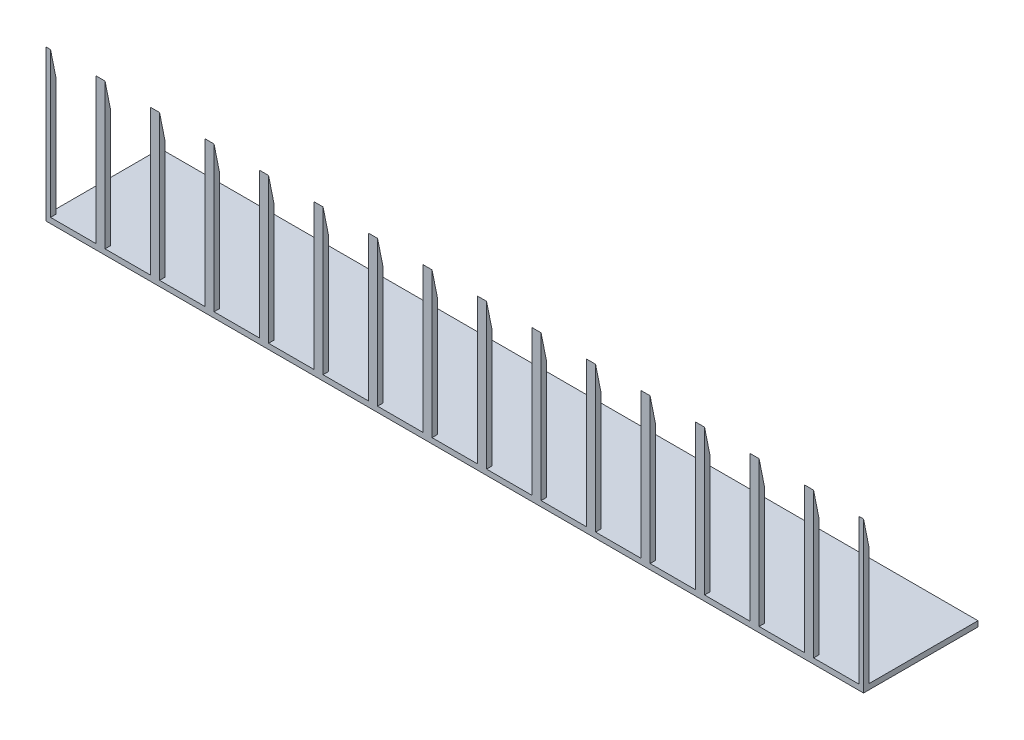
SolidWorks part; units mm, degrees
ref_plane "前视基准面" through (0, 0, 0) normal (0, 0, 1) x (1, 0, 0)
ref_plane "上视基准面" through (0, 0, 0) normal (0, 1, 0) x (1, 0, 0)
ref_plane "右视基准面" through (0, 0, 0) normal (1, 0, 0) x (0, 0, -1)
sketch "草图1" plane through (0, 0, 0) normal (0, 1, 0) x (1, 0, 0)
  line L1 (0, 0) -> (450, 0)
  line L2 (0, 0) -> (0, 60)
  line L3 (0, 60) -> (450, 60)
  line L4 (450, 0) -> (450, 60)
  dimension "D1" = 450
  dimension "D2" = 60
extrude "凸台-拉伸1" add sketch "草图1" along normal blind 3
sketch "草图3" plane through (0, 0, 0) normal (0, 0, 1) x (1, 0, 0)
  line L0 (0, 0) -> (0, 83)
  line L1 (0, 83) -> (2.5, 83)
  line L2 (2.5, 83) -> (2.5, 3)
  line L3 (0, 3) -> (450, 3) construction
  line L4 (2.5, 3) -> (27.5, 3)
  line L5 (27.5, 3) -> (27.5, 83)
  line L6 (27.5, 83) -> (32.5, 83)
  line L7 (32.5, 3) -> (57.5, 3)
  line L8 (57.5, 3) -> (57.5, 83)
  line L9 (32.5, 83) -> (32.5, 3)
  line L10 (57.5, 83) -> (62.5, 83)
  line L11 (62.5, 3) -> (87.5, 3)
  line L12 (87.5, 3) -> (87.5, 83)
  line L13 (62.5, 83) -> (62.5, 3)
  line L14 (87.5, 83) -> (92.5, 83)
  line L15 (92.5, 3) -> (117.5, 3)
  line L16 (117.5, 3) -> (117.5, 83)
  line L17 (92.5, 83) -> (92.5, 3)
  line L18 (117.5, 83) -> (122.5, 83)
  line L19 (122.5, 3) -> (147.5, 3)
  line L20 (147.5, 3) -> (147.5, 83)
  line L21 (122.5, 83) -> (122.5, 3)
  line L22 (147.5, 83) -> (152.5, 83)
  line L23 (152.5, 3) -> (177.5, 3)
  line L24 (177.5, 3) -> (177.5, 83)
  line L25 (152.5, 83) -> (152.5, 3)
  line L26 (177.5, 83) -> (182.5, 83)
  line L27 (182.5, 3) -> (207.5, 3)
  line L28 (207.5, 3) -> (207.5, 83)
  line L29 (182.5, 83) -> (182.5, 3)
  line L30 (207.5, 83) -> (212.5, 83)
  line L31 (212.5, 3) -> (237.5, 3)
  line L32 (237.5, 3) -> (237.5, 83)
  line L33 (212.5, 83) -> (212.5, 3)
  line L34 (237.5, 83) -> (242.5, 83)
  line L35 (242.5, 3) -> (267.5, 3)
  line L36 (267.5, 3) -> (267.5, 83)
  line L37 (242.5, 83) -> (242.5, 3)
  line L38 (267.5, 83) -> (272.5, 83)
  line L39 (272.5, 3) -> (297.5, 3)
  line L40 (297.5, 3) -> (297.5, 83)
  line L41 (272.5, 83) -> (272.5, 3)
  line L42 (297.5, 83) -> (302.5, 83)
  line L43 (302.5, 3) -> (327.5, 3)
  line L44 (327.5, 3) -> (327.5, 83)
  line L45 (302.5, 83) -> (302.5, 3)
  line L46 (327.5, 83) -> (332.5, 83)
  line L47 (332.5, 3) -> (357.5, 3)
  line L48 (357.5, 3) -> (357.5, 83)
  line L49 (332.5, 83) -> (332.5, 3)
  line L50 (357.5, 83) -> (362.5, 83)
  line L51 (362.5, 3) -> (387.5, 3)
  line L52 (387.5, 3) -> (387.5, 83)
  line L53 (362.5, 83) -> (362.5, 3)
  line L54 (387.5, 83) -> (392.5, 83)
  line L55 (392.5, 3) -> (417.5, 3)
  line L56 (417.5, 3) -> (417.5, 83)
  line L57 (392.5, 83) -> (392.5, 3)
  line L58 (417.5, 83) -> (422.5, 83)
  line L60 (422.5, 83) -> (422.5, 3)
  line L61 (422.5, 3) -> (447.5, 3)
  line L62 (447.5, 3) -> (447.5, 83)
  line L63 (450, 83) -> (450, 3)
  line L64 (450, 3) -> (450, 0)
  line L65 (450, 0) -> (0, 0)
  line L66 (447.5, 83) -> (450, 83)
  dimension "D1" = 2.5
  dimension "D2" = 25
  dimension "D3" = 80
  dimension "D4" = 5
  dimension "D5" = 80
  dimension "D8" = 2.5
  dimension "D6" = 14
extrude "凸台-拉伸2" add sketch "草图3" along normal blind 3
sketch "草图4" plane through (0, 0, 0) normal (-1, 0, 0) x (0, 0, 1)
  line L0 (3, 83) -> (0, 68)
  line L1 (0, 83) -> (0, 3) construction
  line L2 (0, 68) -> (0, 83)
  line L3 (0, 83) -> (3, 83)
  dimension "D1" = 15
extrude "切除-拉伸1" cut sketch "草图4" against normal through all
